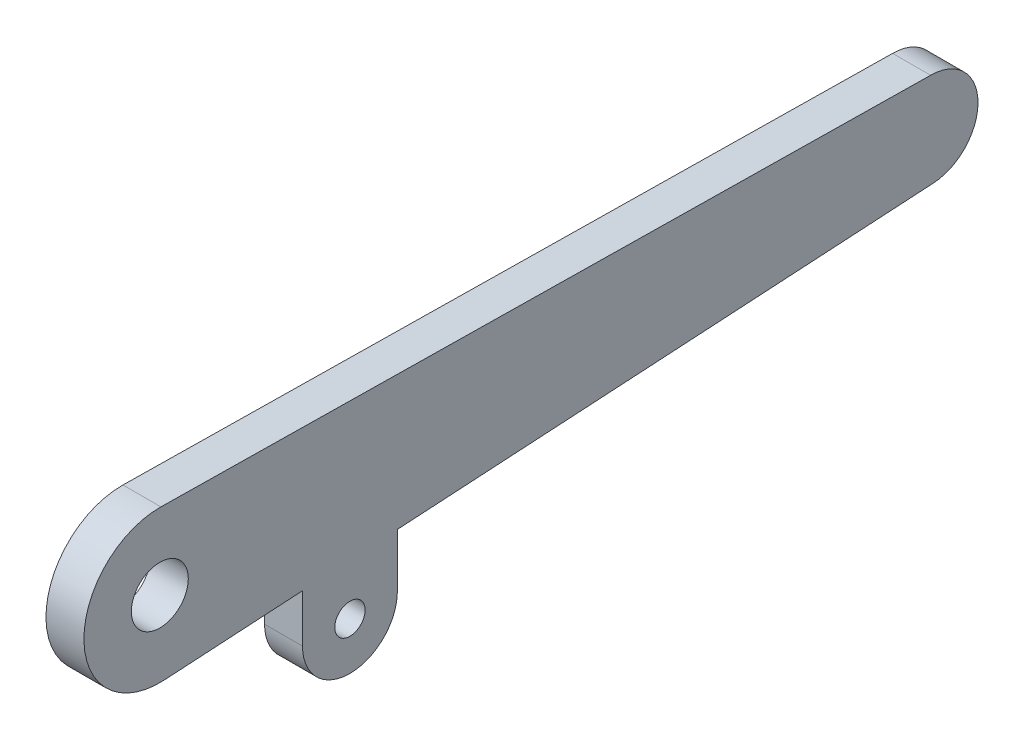
SolidWorks part; units mm, degrees
material "Tough 2000"
ref_plane "Front Plane" through (0, 0, 0) normal (0, 0, 1) x (1, 0, 0)
ref_plane "Top Plane" through (0, 0, 0) normal (0, 1, 0) x (1, 0, 0)
ref_plane "Right Plane" through (0, 0, 0) normal (1, 0, 0) x (0, 0, -1)
sketch "Sketch1" plane through (0, 0, 0) normal (1, 0, 0) x (0, 0, -1)
  line L3 (0.115, 7.9992) -> (81.2455, 6.8327)
  line L4 (0.4755, -7.9859) -> (15.0376, -7.1187)
  line L5 (15.0376, -12.1736) -> (15.0376, -7.1187)
  line L6 (25.0376, -12.1736) -> (25.0376, -6.5232)
  line L7 (25.0376, -6.5232) -> (81.5428, -3.1585)
  arc A0 (0.115, 7.9992) -> (0.4755, -7.9859) centre (0, 0) ccw
  arc A1 (81.5428, -3.1585) -> (81.2455, 6.8327) centre (81.2455, 1.8327) ccw
  arc A2 (15.0376, -12.1736) -> (25.0376, -12.1736) centre (20.0376, -12.1736) ccw
  circle A3 centre (20.0376, -12.1736) radius 1.6
  circle A4 centre (0, 0) radius 3
extrude "Boss-Extrude1" add sketch "Sketch1" along normal blind 4
